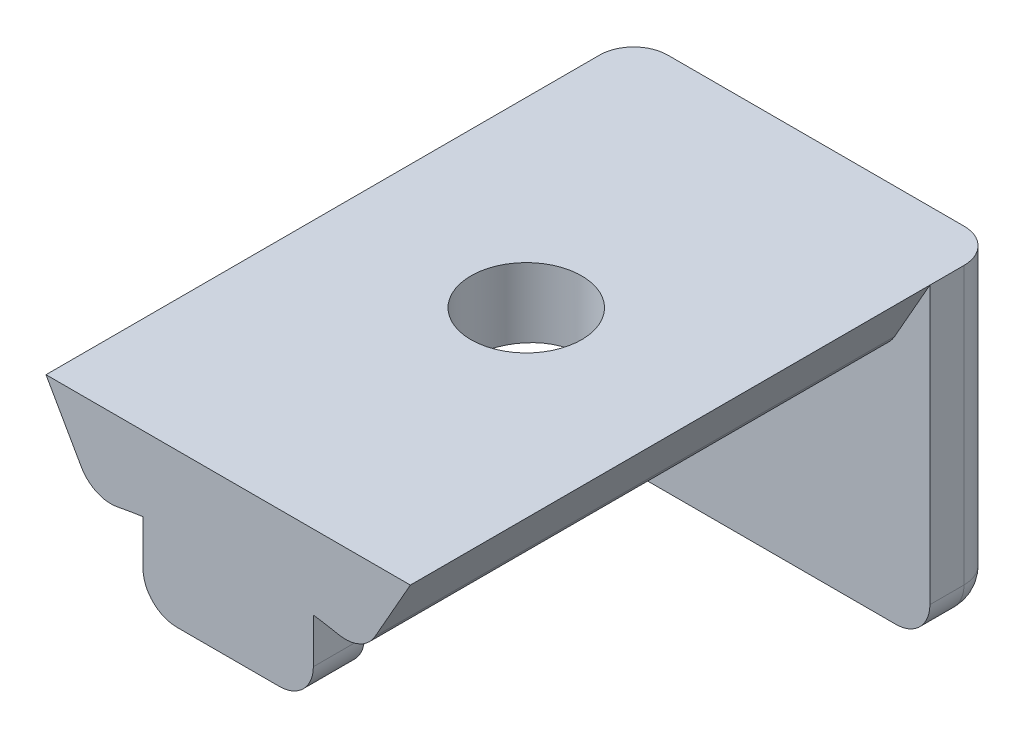
SolidWorks part; units mm, degrees
ref_plane "Front Plane" through (0, 0, 0) normal (0, 0, 1) x (1, 0, 0)
ref_plane "Top Plane" through (0, 0, 0) normal (0, 1, 0) x (1, 0, 0)
ref_plane "Right Plane" through (0, 0, 0) normal (1, 0, 0) x (0, 0, -1)
sketch "Sketch1" plane through (0, 0, 0) normal (0, 0, 1) x (1, 0, 0)
  line L1 (-8.6216, 0.3485) -> (-10.6948, 4)
  line L3 (10.6948, 4) -> (8.6216, 0.3485)
  line L4 (-8.6216, 0.3485) -> (0, -14.8365) construction
  line L5 (0, -14.8365) -> (8.6216, 0.3485) construction
  line L6 (-10.6948, 4) -> (10.6948, 4)
  line L7 (-9.75, 2.336) -> (9.75, 2.336) construction
  arc A0 (6.5, -0.6271) -> (8.6216, 0.3485) centre (6.8824, 1.336) ccw
  arc A1 (-6.5, -0.6271) -> (-8.6216, 0.3485) centre (-6.8824, 1.336) cw
  arc A2 (-6.5, -0.6271) -> (6.5, -0.6271) centre (0, -34) cw
  point P7 (0, 0)
  point P14 (10.6131, 4)
  dimension "D2" = 2
  dimension "D1" = 34
  dimension "D4" = 4
  dimension "D6" = 3
  dimension "D3" = 19.5
  dimension "D5" = 13
extrude "Boss-Extrude1" add sketch "Sketch1" along normal blind 30.5
sketch "Sketch2" plane through (0, 0, 0) normal (0, 0, 1) x (1, 0, 0)
  line L0 (10.6948, 4) -> (10.6948, -12.2476)
  line L1 (8.6948, -14.2476) -> (-8.6948, -14.2476)
  line L2 (8.6216, 0.3485) -> (10.6948, 4)
  line L3 (-10.6948, 4) -> (-8.6216, 0.3485)
  line L6 (-10.6948, -12.2476) -> (-10.6948, 4)
  line L10 (10.6948, 4) -> (-10.6948, 4)
  line L11 (10.6948, 4) -> (-10.6948, 4)
  arc A0 (-8.6948, -14.2476) -> (-10.6948, -12.2476) centre (-8.6948, -12.2476) cw
  arc A1 (10.6948, -12.2476) -> (8.6948, -14.2476) centre (8.6948, -12.2476) cw
  arc A5 (6.5, -0.6271) -> (8.6216, 0.3485) centre (6.8824, 1.336) ccw
  arc A6 (6.5, -0.6271) -> (-6.5, -0.6271) centre (0, -34) ccw
  arc A7 (-8.6216, 0.3485) -> (-6.5, -0.6271) centre (-6.8824, 1.336) ccw
  dimension "D2" = 2
  dimension "D1" = 0
extrude "Boss-Extrude2" add sketch "Sketch2" against normal blind 4
sketch "Sketch3" plane through (0, 0, 0) normal (0, 1, 0) x (1, 0, 0)
  line L0 (0, 0) -> (0, -19.7137) construction
  circle A0 centre (0, -13) radius 3.25
  point P2 (0, 0)
  point P6 (1.3752, -12.9271)
  dimension "D1" = 6.5
  dimension "D2" = 13
  dimension "D3" = 0
extrude "Cut-Extrude1" cut sketch "Sketch3" against normal through all both and the other way through all
sketch "Sketch4" plane through (0, 0, 30.5) normal (0, 0, 1) x (1, 0, 0)
  line L0 (-5, 4) -> (5, 4)
  line L1 (10.6948, 4) -> (-10.6948, 4) construction
  line L2 (5, 4) -> (5, -3)
  line L3 (3, -5) -> (-3, -5)
  line L4 (-5, -3) -> (-5, 4)
  arc A0 (5, -3) -> (3, -5) centre (3, -3) cw
  arc A1 (-3, -5) -> (-5, -3) centre (-3, -3) cw
  point P4 (0, -5)
  dimension "D3" = 2
  dimension "D1" = 10
  dimension "D2" = 9
extrude "Boss-Extrude3" add sketch "Sketch4" against normal offset from surface (3 mm away) 27.5 up to face at (0, -4.6433, 0)
fillet "Fillet2" radius 2 5 edges at (-10.6948, -4.1238, -4) (-10.109, -13.6618, -4) (10.6948, -4.1238, -4) (10.109, -13.6618, -4) (0, -14.2476, -4)
